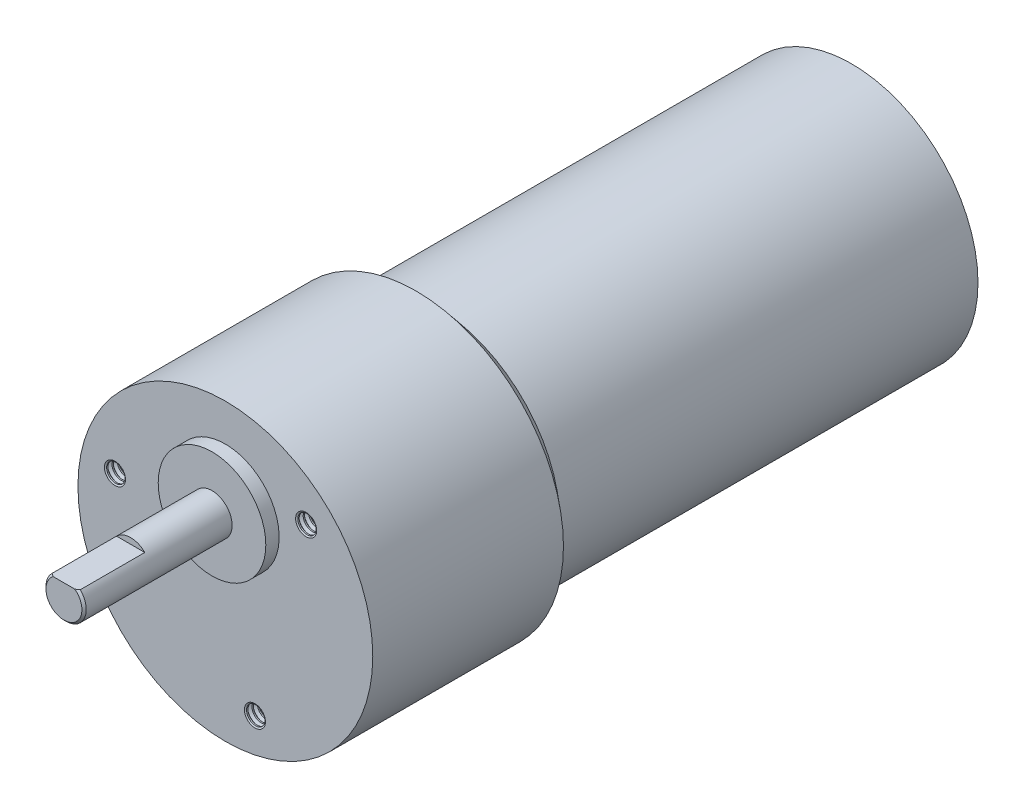
SolidWorks part; units mm, degrees
material "6061 Alloy"
ref_plane "Front" through (0, 0, 0) normal (0, 0, 1) x (1, 0, 0)
ref_plane "Top" through (0, 0, 0) normal (0, 1, 0) x (1, 0, 0)
ref_plane "Right" through (0, 0, 0) normal (1, 0, 0) x (0, 0, -1)
sketch "Sketch1" plane through (0, 0, 0) normal (0, 0, 1) x (1, 0, 0)
  circle A0 centre (0, 6.6548) radius 6.35
  dimension "D1" = 12.7
  dimension "D2" = 6.6548
extrude "Extrude1" add sketch "Sketch1" along normal blind 1.5748
sketch "Sketch2" plane through (0, 0, 0) normal (0, 0, -1) x (-1, 0, 0)
  circle A3 centre (0, 0) radius 14.9225
  dimension "D1" = 29.845
extrude "Extrude2" add sketch "Sketch2" along normal blind 73.914
sketch "Sketch3" plane through (0, 0, 0) normal (0, 0, 1) x (1, 0, 0)
  circle A0 centre (0, 6.6548) radius 2.3749
  circle A1 centre (0, 6.6548) radius 6.35 construction
  dimension "D1" = 4.7498
extrude "Extrude3" add sketch "Sketch3" along normal blind 19.05
sketch "Sketch9" plane through (0, 0, 0) normal (1, 0, 0) x (0, 0, -1)
  line L0 (51.187, 0) -> (68.6952, 0) construction
  line L1 (73.914, 0) -> (73.914, 6.35)
  line L2 (73.914, 6.35) -> (75.4888, 6.35)
  line L3 (75.4888, 6.35) -> (75.4888, 1.9812)
  line L4 (75.4888, 1.9812) -> (76.7588, 1.9812)
  line L5 (76.7588, 1.9812) -> (76.7588, 0)
  line L6 (76.7588, 0) -> (73.914, 0)
  line L7 (73.914, -14.9225) -> (73.914, 14.9225) construction
  dimension "D1" = 1.5748
  dimension "D2" = 1.27
  dimension "D3" = 3.9624
  dimension "D4" = 12.7
revolve "Revolve1" add sketch "Sketch9" angle 360 about L0
sketch "Sketch10" plane through (0, 0, 0) normal (1, 0, 0) x (0, 0, -1)
  line L0 (73.914, -14.9225) -> (73.914, 14.9225) construction
  line L1 (63.246, 22.098) -> (66.04, 22.098)
  line L2 (63.246, 22.098) -> (63.246, 0)
  line L3 (63.246, 0) -> (66.04, 0)
  line L4 (66.04, 22.098) -> (66.04, 0)
  line L5 (73.914, 0) -> (0, 0) construction
  circle A0 centre (64.643, 20.193) radius 0.5969
  point P4 (64.643, 22.098)
  dimension "D4" = 1.1938
  dimension "D5" = 1.905
  dimension "D1" = 9.271
  dimension "D2" = 2.794
  dimension "D3" = 22.098
extrude "Extrude5" [suppressed] add sketch "Sketch10" along normal mid plane 6.096
sketch "Sketch11" [suppressed] plane through (0, 0, -63.246) normal (0, 0, 1) x (1, 0, 0)
  line L0 (-2.6416, 22.098) -> (-2.6416, 14.6868)
  line L1 (-2.6416, 22.098) -> (2.6416, 22.098)
  line L2 (2.6416, 22.098) -> (2.6416, 14.6868)
  line L3 (3.048, 22.098) -> (-3.048, 22.098) construction
  line L4 (3.048, 22.098) -> (3.048, 14.6079) construction
  circle A0 centre (0, 0) radius 14.9225 construction
  arc A1 (2.6416, 14.6868) -> (-2.6416, 14.6868) centre (0, 0) ccw
  dimension "D1" = 0.4064
extrude "Cut-Extrude2" [suppressed] cut sketch "Sketch11" against normal through all
sketch "Sketch12" plane through (0, 0, 0) normal (1, 0, 0) x (0, 0, -1)
  line L0 (59.9884, 14.9225) -> (62.738, 16.51)
  line L1 (62.738, 16.51) -> (66.548, 16.51)
  line L2 (66.548, 16.51) -> (66.548, 14.9225)
  line L3 (66.548, 14.9225) -> (59.9884, 14.9225)
  line L5 (63.246, 22.098) -> (66.04, 22.098) construction
  line L8 (71.361, 0) -> (26.4089, 0) construction
  line L9 (73.914, 0) -> (0, 0) construction
  line L10 (66.04, 22.098) -> (66.04, 0) construction
  line L11 (63.246, 22.098) -> (63.246, 0) construction
  line L12 (63.246, 22.098) -> (66.04, 22.098) construction
  line L13 (66.04, 22.098) -> (66.04, 0) construction
  line L14 (63.246, 22.098) -> (63.246, 0) construction
  line L15 (73.914, 14.9225) -> (0, 14.9225) construction
  circle A0 centre (64.643, 20.193) radius 0.5969 construction
  circle A1 centre (64.643, 20.193) radius 0.5969 construction
  dimension "D1" = 16.51
  dimension "D2" = 0.508
  dimension "D3" = 0.508
  dimension "D4" = 30
revolve "Revolve2" [suppressed] add sketch "Sketch12" angle 90 mid plane about L8
sketch "Sketch13" plane through (0, 0, 0) normal (1, 0, 0) x (0, 0, -1)
  line L0 (0, 14.9225) -> (0, 17.399)
  line L1 (0, 17.399) -> (22.5092, 17.399)
  line L2 (22.5092, 17.399) -> (24.5872, 14.9225)
  line L3 (24.5872, 14.9225) -> (0, 14.9225)
  line L5 (-4.8199, 0) -> (14.8134, 0) construction
  line L6 (73.914, 0) -> (0, 0) construction
  line L7 (0, -14.9225) -> (0, 14.9225) construction
  dimension "D1" = 34.798
  dimension "D2" = 24.5872
  dimension "D3" = 50
revolve "Revolve3" add sketch "Sketch13" angle 360 about L5
ref_plane "Plane1" through (0, 0, 0) normal (0.9659, 0.2588, 0) x (0, 0, -1)
sketch "Sketch7" plane through (0, 0, 0) normal (-0.9659, -0.2588, 0) x (0, 0, -1)
  line L0 (-15.8213, 0) -> (8.2348, 0) construction
  line L1 (-0.2187, 13.4874) -> (5.9824, 13.4874) construction
  line L2 (-0.381, 13.4874) -> (5.334, 13.4874)
  line L3 (5.334, 13.4874) -> (5.334, 14.5661)
  line L4 (5.334, 14.5661) -> (5.1752, 14.5661)
  line L5 (5.1752, 14.5661) -> (4.9768, 14.9098)
  line L6 (4.9768, 14.9098) -> (4.8974, 14.9098)
  line L7 (4.8974, 14.9098) -> (4.699, 14.5661)
  line L8 (4.699, 14.5661) -> (5.1752, 14.5661) construction
  line L9 (4.9371, 14.5661) -> (4.9371, 14.9098) construction
  line L10 (-0.1826, 14.9098) -> (-0.381, 14.5661)
  line L11 (4.2624, 14.9098) -> (4.064, 14.5661)
  line L12 (4.3418, 14.9098) -> (4.2624, 14.9098)
  line L13 (4.5402, 14.5661) -> (4.3418, 14.9098)
  line L14 (4.699, 14.5661) -> (4.5402, 14.5661)
  line L15 (3.6274, 14.9098) -> (3.429, 14.5661)
  line L16 (3.7068, 14.9098) -> (3.6274, 14.9098)
  line L17 (3.9052, 14.5661) -> (3.7068, 14.9098)
  line L18 (4.064, 14.5661) -> (3.9052, 14.5661)
  line L19 (2.9924, 14.9098) -> (2.794, 14.5661)
  line L20 (3.0718, 14.9098) -> (2.9924, 14.9098)
  line L21 (3.2702, 14.5661) -> (3.0718, 14.9098)
  line L22 (3.429, 14.5661) -> (3.2702, 14.5661)
  line L23 (2.3574, 14.9098) -> (2.159, 14.5661)
  line L24 (2.4368, 14.9098) -> (2.3574, 14.9098)
  line L25 (2.6352, 14.5661) -> (2.4368, 14.9098)
  line L26 (2.794, 14.5661) -> (2.6352, 14.5661)
  line L27 (1.7224, 14.9098) -> (1.524, 14.5661)
  line L28 (1.8018, 14.9098) -> (1.7224, 14.9098)
  line L29 (2.0002, 14.5661) -> (1.8018, 14.9098)
  line L30 (2.159, 14.5661) -> (2.0002, 14.5661)
  line L31 (1.0874, 14.9098) -> (0.889, 14.5661)
  line L32 (1.1668, 14.9098) -> (1.0874, 14.9098)
  line L33 (1.3652, 14.5661) -> (1.1668, 14.9098)
  line L34 (1.524, 14.5661) -> (1.3652, 14.5661)
  line L35 (0.4524, 14.9098) -> (0.254, 14.5661)
  line L36 (0.5318, 14.9098) -> (0.4524, 14.9098)
  line L37 (0.7302, 14.5661) -> (0.5318, 14.9098)
  line L38 (0.889, 14.5661) -> (0.7302, 14.5661)
  line L40 (0, 14.9225) -> (0, -14.9225) construction
  line L41 (-0.1032, 14.9098) -> (-0.1826, 14.9098)
  line L42 (0.0952, 14.5661) -> (-0.1032, 14.9098)
  line L43 (0.254, 14.5661) -> (0.0952, 14.5661)
  line L44 (-0.381, 14.5661) -> (-0.381, 13.4874)
  dimension "D1" = 5.334
  dimension "D2" = 2.8448
  dimension "D3" = 0.635
  dimension "D4" = 60
  dimension "D5" = 0.1588
  dimension "D6" = 0.0794
  dimension "D7" = 26.9748
revolve "Cut-Revolve1" cut sketch "Sketch7" angle 360 about L1
pattern_circular "CirPattern1" count 3 over 360 about axis through (0, 0, 0) along (0, 0, 1) of "Cut-Revolve1"
sketch "Sketch14" plane through (0, 0, 19.05) normal (0, 0, 1) x (1, 0, 0)
  line L1 (-1.6695, 9.0297) -> (1.6695, 9.0297)
  line L2 (-1.6695, 9.0297) -> (-1.6695, 8.3439)
  line L3 (-1.6695, 8.3439) -> (1.6695, 8.3439)
  line L4 (1.6695, 9.0297) -> (1.6695, 8.3439)
  circle A0 centre (0, 6.6548) radius 2.3749 construction
  dimension "D1" = 4.064
extrude "Cut-Extrude3" cut sketch "Sketch14" against normal blind 7.874
chamfer "Chamfer1" distance 0.254 angle 45 2 edges at (0, 4.2799, 19.05) (1.9812, 0, -76.7588)
